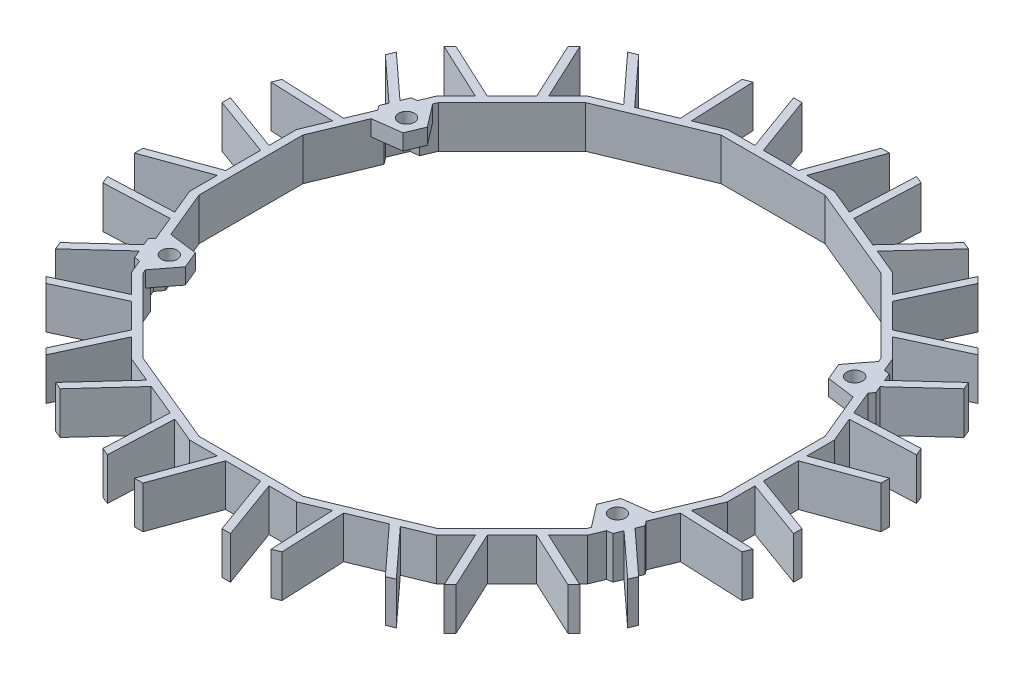
SolidWorks part; units mm, degrees
ref_plane "Front Plane" through (0, 0, 0) normal (0, 0, 1) x (1, 0, 0)
ref_plane "Top Plane" through (0, 0, 0) normal (0, 1, 0) x (1, 0, 0)
ref_plane "Right Plane" through (0, 0, 0) normal (1, 0, 0) x (0, 0, -1)
sketch "Sketch1" plane through (0, 0, 0) normal (0, 1, 0) x (1, 0, 0)
  line L1 (62.5, 12.432) -> (52.9849, 35.4034)
  line L2 (52.9849, 35.4034) -> (35.4034, 52.9849)
  line L3 (35.4034, 52.9849) -> (12.432, 62.5)
  line L4 (12.432, 62.5) -> (-12.432, 62.5)
  line L5 (-12.432, 62.5) -> (-35.4034, 52.9849)
  line L6 (-35.4034, 52.9849) -> (-52.9849, 35.4034)
  line L7 (-52.9849, 35.4034) -> (-62.5, 12.432)
  line L8 (-62.5, 12.432) -> (-62.5, -12.432)
  line L9 (-62.5, -12.432) -> (-52.9849, -35.4034)
  line L10 (-52.9849, -35.4034) -> (-35.4034, -52.9849)
  line L11 (-35.4034, -52.9849) -> (-12.432, -62.5)
  line L12 (-12.432, -62.5) -> (12.432, -62.5)
  line L13 (12.432, -62.5) -> (35.4034, -52.9849)
  line L14 (35.4034, -52.9849) -> (52.9849, -35.4034)
  line L15 (52.9849, -35.4034) -> (62.5, -12.432)
  line L16 (62.5, -12.432) -> (62.5, 12.432)
  circle A0 centre (0, 0) radius 62.5 construction
  dimension "D1" = 125
extrude "Boss-Extrude1" add sketch "Sketch1" along normal blind 1.6
sketch "Sketch2" plane through (0, 0, 0) normal (0, -1, 0) x (1, 0, 0)
  line L0 (-7.5, 62.5) -> (-3.3143, 51)
  line L1 (-12.432, 62.5) -> (12.432, 62.5) construction
  line L2 (-3.3143, 51) -> (3.3143, 51)
  line L3 (3.3143, 51) -> (7.5, 62.5)
  line L4 (7.5, 62.5) -> (9.0963, 62.5)
  line L5 (9.0963, 62.5) -> (4.3647, 49.5)
  line L6 (4.3647, 49.5) -> (-4.3647, 49.5)
  line L7 (-4.3647, 49.5) -> (-9.0963, 62.5)
  line L8 (-9.0963, 62.5) -> (-7.5, 62.5)
  line L131 (15.5139, 61.2235) -> (16.9886, 60.6126)
  line L132 (16.9886, 60.6126) -> (16.4548, 48.3862)
  line L133 (16.4548, 48.3862) -> (22.5789, 45.8495)
  line L134 (22.5789, 45.8495) -> (30.8468, 54.8723)
  line L135 (30.8468, 54.8723) -> (32.3216, 54.2615)
  line L136 (32.3216, 54.2615) -> (22.9752, 44.0618)
  line L137 (22.9752, 44.0618) -> (14.9104, 47.4023)
  line L138 (14.9104, 47.4023) -> (15.5139, 61.2235)
  line L139 (37.7621, 50.6262) -> (38.8909, 49.4975)
  line L140 (38.8909, 49.4975) -> (33.7189, 38.406)
  line L141 (33.7189, 38.406) -> (38.406, 33.7189)
  line L142 (38.406, 33.7189) -> (49.4975, 38.8909)
  line L143 (49.4975, 38.8909) -> (50.6262, 37.7621)
  line L144 (50.6262, 37.7621) -> (38.0881, 31.9155)
  line L145 (38.0881, 31.9155) -> (31.9155, 38.0881)
  line L146 (31.9155, 38.0881) -> (37.7621, 50.6262)
  line L147 (54.2615, 32.3216) -> (54.8723, 30.8468)
  line L148 (54.8723, 30.8468) -> (45.8495, 22.5789)
  line L149 (45.8495, 22.5789) -> (48.3862, 16.4548)
  line L150 (48.3862, 16.4548) -> (60.6126, 16.9886)
  line L151 (60.6126, 16.9886) -> (61.2235, 15.5139)
  line L152 (61.2235, 15.5139) -> (47.4023, 14.9104)
  line L153 (47.4023, 14.9104) -> (44.0618, 22.9752)
  line L154 (44.0618, 22.9752) -> (54.2615, 32.3216)
  line L155 (62.5, 9.0963) -> (62.5, 7.5)
  line L156 (62.5, 7.5) -> (51, 3.3143)
  line L157 (51, 3.3143) -> (51, -3.3143)
  line L158 (51, -3.3143) -> (62.5, -7.5)
  line L167 (62.5, -7.5) -> (62.5, -9.0963)
  line L184 (62.5, -9.0963) -> (49.5, -4.3647)
  line L185 (49.5, -4.3647) -> (49.5, 4.3647)
  line L186 (49.5, 4.3647) -> (62.5, 9.0963)
  line L187 (61.2235, -15.5139) -> (60.6126, -16.9886)
  line L188 (60.6126, -16.9886) -> (48.3862, -16.4548)
  line L189 (48.3862, -16.4548) -> (45.8495, -22.5789)
  line L190 (45.8495, -22.5789) -> (54.8723, -30.8468)
  line L191 (54.8723, -30.8468) -> (54.2615, -32.3216)
  line L192 (54.2615, -32.3216) -> (44.0618, -22.9752)
  line L193 (44.0618, -22.9752) -> (47.4023, -14.9104)
  line L194 (47.4023, -14.9104) -> (61.2235, -15.5139)
  line L195 (50.6262, -37.7621) -> (49.4975, -38.8909)
  line L196 (49.4975, -38.8909) -> (38.406, -33.7189)
  line L197 (38.406, -33.7189) -> (33.7189, -38.406)
  line L198 (33.7189, -38.406) -> (38.8909, -49.4975)
  line L199 (38.8909, -49.4975) -> (37.7621, -50.6262)
  line L200 (37.7621, -50.6262) -> (31.9155, -38.0881)
  line L201 (31.9155, -38.0881) -> (38.0881, -31.9155)
  line L202 (38.0881, -31.9155) -> (50.6262, -37.7621)
  line L203 (32.3216, -54.2615) -> (30.8468, -54.8723)
  line L204 (30.8468, -54.8723) -> (22.5789, -45.8495)
  line L205 (22.5789, -45.8495) -> (16.4548, -48.3862)
  line L206 (16.4548, -48.3862) -> (16.9886, -60.6126)
  line L207 (16.9886, -60.6126) -> (15.5139, -61.2235)
  line L208 (15.5139, -61.2235) -> (14.9104, -47.4023)
  line L209 (14.9104, -47.4023) -> (22.9752, -44.0618)
  line L210 (22.9752, -44.0618) -> (32.3216, -54.2615)
  line L211 (9.0963, -62.5) -> (7.5, -62.5)
  line L212 (7.5, -62.5) -> (3.3143, -51)
  line L213 (3.3143, -51) -> (-3.3143, -51)
  line L214 (-3.3143, -51) -> (-7.5, -62.5)
  line L215 (-7.5, -62.5) -> (-9.0963, -62.5)
  line L216 (-9.0963, -62.5) -> (-4.3647, -49.5)
  line L217 (-4.3647, -49.5) -> (4.3647, -49.5)
  line L218 (4.3647, -49.5) -> (9.0963, -62.5)
  line L219 (-15.5139, -61.2235) -> (-16.9886, -60.6126)
  line L220 (-16.9886, -60.6126) -> (-16.4548, -48.3862)
  line L221 (-16.4548, -48.3862) -> (-22.5789, -45.8495)
  line L222 (-22.5789, -45.8495) -> (-30.8468, -54.8723)
  line L223 (-30.8468, -54.8723) -> (-32.3216, -54.2615)
  line L224 (-32.3216, -54.2615) -> (-22.9752, -44.0618)
  line L225 (-22.9752, -44.0618) -> (-14.9104, -47.4023)
  line L226 (-14.9104, -47.4023) -> (-15.5139, -61.2235)
  line L227 (-37.7621, -50.6262) -> (-38.8909, -49.4975)
  line L228 (-38.8909, -49.4975) -> (-33.7189, -38.406)
  line L229 (-33.7189, -38.406) -> (-38.406, -33.7189)
  line L230 (-38.406, -33.7189) -> (-49.4975, -38.8909)
  line L231 (-49.4975, -38.8909) -> (-50.6262, -37.7621)
  line L232 (-50.6262, -37.7621) -> (-38.0881, -31.9155)
  line L233 (-38.0881, -31.9155) -> (-31.9155, -38.0881)
  line L234 (-31.9155, -38.0881) -> (-37.7621, -50.6262)
  line L235 (-54.2615, -32.3216) -> (-54.8723, -30.8468)
  line L236 (-54.8723, -30.8468) -> (-45.8495, -22.5789)
  line L237 (-45.8495, -22.5789) -> (-48.3862, -16.4548)
  line L238 (-48.3862, -16.4548) -> (-60.6126, -16.9886)
  line L239 (-60.6126, -16.9886) -> (-61.2235, -15.5139)
  line L240 (-61.2235, -15.5139) -> (-47.4023, -14.9104)
  line L241 (-47.4023, -14.9104) -> (-44.0618, -22.9752)
  line L242 (-44.0618, -22.9752) -> (-54.2615, -32.3216)
  line L243 (-62.5, -9.0963) -> (-62.5, -7.5)
  line L244 (-62.5, -7.5) -> (-51, -3.3143)
  line L245 (-51, -3.3143) -> (-51, 3.3143)
  line L246 (-51, 3.3143) -> (-62.5, 7.5)
  line L247 (-62.5, 7.5) -> (-62.5, 9.0963)
  line L248 (-62.5, 9.0963) -> (-49.5, 4.3647)
  line L249 (-49.5, 4.3647) -> (-49.5, -4.3647)
  line L250 (-49.5, -4.3647) -> (-62.5, -9.0963)
  line L251 (-61.2235, 15.5139) -> (-60.6126, 16.9886)
  line L252 (-60.6126, 16.9886) -> (-48.3862, 16.4548)
  line L253 (-48.3862, 16.4548) -> (-45.8495, 22.5789)
  line L254 (-45.8495, 22.5789) -> (-54.8723, 30.8468)
  line L255 (-54.8723, 30.8468) -> (-54.2615, 32.3216)
  line L256 (-54.2615, 32.3216) -> (-44.0618, 22.9752)
  line L257 (-44.0618, 22.9752) -> (-47.4023, 14.9104)
  line L258 (-47.4023, 14.9104) -> (-61.2235, 15.5139)
  line L259 (-50.6262, 37.7621) -> (-49.4975, 38.8909)
  line L260 (-49.4975, 38.8909) -> (-38.406, 33.7189)
  line L261 (-38.406, 33.7189) -> (-33.7189, 38.406)
  line L262 (-33.7189, 38.406) -> (-38.8909, 49.4975)
  line L263 (-38.8909, 49.4975) -> (-37.7621, 50.6262)
  line L264 (-37.7621, 50.6262) -> (-31.9155, 38.0881)
  line L265 (-31.9155, 38.0881) -> (-38.0881, 31.9155)
  line L266 (-38.0881, 31.9155) -> (-50.6262, 37.7621)
  line L267 (-32.3216, 54.2615) -> (-30.8468, 54.8723)
  line L268 (-30.8468, 54.8723) -> (-22.5789, 45.8495)
  line L269 (-22.5789, 45.8495) -> (-16.4548, 48.3862)
  line L270 (-16.4548, 48.3862) -> (-16.9886, 60.6126)
  line L271 (-16.9886, 60.6126) -> (-15.5139, 61.2235)
  line L272 (-15.5139, 61.2235) -> (-14.9104, 47.4023)
  line L273 (-14.9104, 47.4023) -> (-22.9752, 44.0618)
  line L274 (-22.9752, 44.0618) -> (-32.3216, 54.2615)
  point P4 (0, 51)
  point P11 (0, 49.5)
  point P136 (0, 0)
  point P138 (0, 0)
  dimension "D6" = 16
  dimension "D1" = 1.5
  dimension "D2" = 1.5
  dimension "D3" = 15
  dimension "D4" = 40
  dimension "D5" = 11.5
extrude "Boss-Extrude5" add sketch "Sketch2" along normal blind 8
sketch "Sketch6" plane through (0, 1.6, 0) normal (0, 1, 0) x (1, 0, 0)
  line L1 (-42.5, -22.5) -> (42.5, -22.5) construction
  line L2 (-42.5, -22.5) -> (-42.5, 22.5) construction
  line L3 (-42.5, 22.5) -> (42.5, 22.5) construction
  line L4 (42.5, -22.5) -> (42.5, 22.5) construction
  line L5 (-42.5, -22.5) -> (42.5, 22.5) construction
  line L6 (-42.5, 22.5) -> (42.5, -22.5) construction
  circle A0 centre (-42.5, 22.5) radius 1.5
  circle A1 centre (-42.5, -22.5) radius 1.5
  circle A2 centre (42.5, -22.5) radius 1.5
  circle A3 centre (42.5, 22.5) radius 1.5
  point P0 (0, 0)
  dimension "D3" = 3
  dimension "D1" = 85
  dimension "D2" = 45
extrude "Cut-Extrude2" cut sketch "Sketch6" against normal up to surface (1.6 mm away) up to face at (0, 0, 0)
sketch "Sketch17" plane through (0, -8, 0) normal (0, -1, 0) x (1, 0, 0)
  line L1 (-9.8462, 49.5) -> (-28.0395, 41.9641)
  line L2 (-28.0395, 41.9641) -> (-41.9641, 28.0395)
  line L3 (-41.9641, 28.0395) -> (-49.5, 9.8462)
  line L4 (-49.5, 9.8462) -> (-49.5, -9.8462)
  line L5 (-49.5, -9.8462) -> (-41.9641, -28.0395)
  line L6 (-41.9641, -28.0395) -> (-28.0395, -41.9641)
  line L7 (-28.0395, -41.9641) -> (-9.8462, -49.5)
  line L8 (-9.8462, -49.5) -> (9.8462, -49.5)
  line L9 (9.8462, -49.5) -> (28.0395, -41.9641)
  line L10 (28.0395, -41.9641) -> (41.9641, -28.0395)
  line L11 (41.9641, -28.0395) -> (49.5, -9.8462)
  line L12 (49.5, -9.8462) -> (49.5, 9.8462)
  line L13 (49.5, 9.8462) -> (41.9641, 28.0395)
  line L14 (41.9641, 28.0395) -> (28.0395, 41.9641)
  line L15 (28.0395, 41.9641) -> (9.8462, 49.5)
  line L16 (9.8462, 49.5) -> (-9.8462, 49.5)
  line L18 (-49.5, -4.3647) -> (-49.5, 4.3647) construction
  line L20 (-10.1445, 51) -> (-28.8892, 43.2357)
  line L21 (-28.8892, 43.2357) -> (-43.2357, 28.8892)
  line L22 (-43.2357, 28.8892) -> (-51, 10.1445)
  line L23 (-51, 10.1445) -> (-51, -10.1445)
  line L24 (-51, -10.1445) -> (-43.2357, -28.8892)
  line L25 (-43.2357, -28.8892) -> (-28.8892, -43.2357)
  line L26 (-28.8892, -43.2357) -> (-10.1445, -51)
  line L27 (-10.1445, -51) -> (10.1445, -51)
  line L28 (10.1445, -51) -> (28.8892, -43.2357)
  line L29 (28.8892, -43.2357) -> (43.2357, -28.8892)
  line L30 (43.2357, -28.8892) -> (51, -10.1445)
  line L31 (51, -10.1445) -> (51, 10.1445)
  line L32 (51, 10.1445) -> (43.2357, 28.8892)
  line L33 (43.2357, 28.8892) -> (28.8892, 43.2357)
  line L34 (28.8892, 43.2357) -> (10.1445, 51)
  line L35 (10.1445, 51) -> (-10.1445, 51)
  line L36 (-51, 3.3143) -> (-51, -3.3143) construction
  circle A0 centre (0, 0) radius 49.5 construction
  circle A1 centre (0, 0) radius 51 construction
extrude "Boss-Extrude9" add sketch "Sketch17" against normal up to surface (8 mm away) up to face at (-56.75, 0, 0)
sketch "Sketch16" plane through (0, -8, 0) normal (0, -1, 0) x (1, 0, 0)
  line L0 (-49.5, 9.8462) -> (-41.9641, 28.0395) construction
  line L1 (-43.8477, 19.2462) -> (-40.356, 19.7059)
  line L2 (-40.356, 19.7059) -> (-39.0083, 22.9597)
  line L3 (-39.0083, 22.9597) -> (-41.1523, 25.7538)
  line L4 (-41.1523, 25.7538) -> (-44.644, 25.2941)
  line L5 (-44.644, 25.2941) -> (-45.9917, 22.0403)
  line L6 (-45.9917, 22.0403) -> (-43.8477, 19.2462)
  line L7 (0, -0.88) -> (0, 0.88) construction
  line L8 (45.9917, 22.0403) -> (43.8477, 19.2462)
  line L9 (44.644, 25.2941) -> (45.9917, 22.0403)
  line L10 (41.1523, 25.7538) -> (44.644, 25.2941)
  line L11 (39.0083, 22.9597) -> (41.1523, 25.7538)
  line L12 (40.356, 19.7059) -> (39.0083, 22.9597)
  line L13 (43.8477, 19.2462) -> (40.356, 19.7059)
  line L14 (0.88, 0) -> (-0.88, 0) construction
  line L15 (44.644, -25.2941) -> (45.9917, -22.0403)
  line L16 (41.1523, -25.7538) -> (44.644, -25.2941)
  line L17 (39.0083, -22.9597) -> (41.1523, -25.7538)
  line L18 (40.356, -19.7059) -> (39.0083, -22.9597)
  line L19 (43.8477, -19.2462) -> (40.356, -19.7059)
  line L20 (45.9917, -22.0403) -> (43.8477, -19.2462)
  line L21 (-45.9917, -22.0403) -> (-43.8477, -19.2462)
  line L22 (-44.644, -25.2941) -> (-45.9917, -22.0403)
  line L23 (-41.1523, -25.7538) -> (-44.644, -25.2941)
  line L24 (-39.0083, -22.9597) -> (-41.1523, -25.7538)
  line L25 (-40.356, -19.7059) -> (-39.0083, -22.9597)
  line L26 (-43.8477, -19.2462) -> (-40.356, -19.7059)
  circle A0 centre (-42.5, 22.5) radius 3.05 construction
  dimension "D1" = 6.1
extrude "Cut-Extrude5" cut sketch "Sketch16" against normal up to surface (8 mm away) up to face at (42.5, 0, -21)
sketch "Sketch21" plane through (0, 0, 0) normal (0, -1, 0) x (1, 0, 0)
  line L0 (-44.644, 25.2941) -> (-45.9917, 22.0403) construction
  line L1 (-47.1365, 21.8896) -> (-45.4317, 19.6678)
  line L5 (-42.5704, 26.5757) -> (-45.3469, 26.2101)
  line L6 (-45.3469, 26.2101) -> (-47.1365, 21.8896)
  line L7 (-45.9917, 22.0403) -> (-44.9898, 20.7347)
  line L11 (-43.0123, 25.5089) -> (-44.644, 25.2941)
  line L12 (-44.644, 25.2941) -> (-45.9917, 22.0403)
  line L13 (-43.0123, 25.5089) -> (-42.5704, 26.5757)
  line L15 (-43.0123, 25.5089) -> (-41.9641, 28.0395) construction
  line L16 (-44.9898, 20.7347) -> (-45.4317, 19.6678)
  line L17 (-49.5, 9.8462) -> (-44.9898, 20.7347) construction
  line L18 (0, -0.88) -> (0, 0.88) construction
  line L19 (-42.1019, 19.4761) -> (-40.356, 19.7059) [skipped]
  line L20 (-41.9714, 18.4846) -> (-39.6531, 18.7899) [skipped]
  line L21 (-38.7583, 20.9501) -> (-37.8635, 23.1104) [skipped]
  line L22 (-39.6822, 21.3328) -> (-39.0083, 22.9597) [skipped]
  line L23 (-39.0083, 22.9597) -> (-41.1523, 25.7538) [skipped]
  line L24 (-37.8635, 23.1104) -> (-40.7104, 26.8206) [skipped]
  line L25 (43.0123, 25.5089) -> (42.5704, 26.5757)
  line L26 (42.5704, 26.5757) -> (45.3469, 26.2101)
  line L27 (45.3469, 26.2101) -> (47.1365, 21.8896)
  line L28 (47.1365, 21.8896) -> (45.4317, 19.6678)
  line L29 (44.9898, 20.7347) -> (45.4317, 19.6678)
  line L30 (45.9917, 22.0403) -> (44.9898, 20.7347)
  line L31 (44.644, 25.2941) -> (45.9917, 22.0403)
  line L32 (43.0123, 25.5089) -> (44.644, 25.2941)
  line L33 (0.88, 0) -> (-0.88, 0) construction
  line L34 (43.0123, -25.5089) -> (44.644, -25.2941)
  line L35 (44.644, -25.2941) -> (45.9917, -22.0403)
  line L36 (45.9917, -22.0403) -> (44.9898, -20.7347)
  line L37 (44.9898, -20.7347) -> (45.4317, -19.6678)
  line L38 (47.1365, -21.8896) -> (45.4317, -19.6678)
  line L39 (45.3469, -26.2101) -> (47.1365, -21.8896)
  line L40 (42.5704, -26.5757) -> (45.3469, -26.2101)
  line L41 (43.0123, -25.5089) -> (42.5704, -26.5757)
  line L42 (-44.9898, -20.7347) -> (-45.4317, -19.6678)
  line L43 (-43.0123, -25.5089) -> (-42.5704, -26.5757)
  line L44 (-44.644, -25.2941) -> (-45.9917, -22.0403)
  line L45 (-43.0123, -25.5089) -> (-44.644, -25.2941)
  line L46 (-45.9917, -22.0403) -> (-44.9898, -20.7347)
  line L47 (-45.3469, -26.2101) -> (-47.1365, -21.8896)
  line L48 (-42.5704, -26.5757) -> (-45.3469, -26.2101)
  line L49 (-47.1365, -21.8896) -> (-45.4317, -19.6678)
  arc A0 (-42.5814, 26.5492) -> (-45.4208, 19.6943) centre (-42.5, 22.5) ccw construction
  arc A1 (-42.5814, -26.5492) -> (-45.4208, -19.6943) centre (-42.5, -22.5) cw construction
  dimension "D1" = 1
extrude "Boss-Extrude11" add sketch "Sketch21" along normal up to surface (8 mm away) up to face at (0, -8, 0)
sketch "Sketch22" plane through (0, 0, 0) normal (0, -1, 0) x (1, 0, 0)
  line L0 (45.9917, 22.0403) -> (44.644, 25.2941) construction
  line L1 (44.644, 25.2941) -> (41.1523, 25.7538)
  line L2 (41.1523, 25.7538) -> (39.0083, 22.9597)
  line L3 (39.0083, 22.9597) -> (40.356, 19.7059)
  line L4 (40.356, 19.7059) -> (43.8477, 19.2462)
  line L5 (43.8477, 19.2462) -> (45.9917, 22.0403)
  line L6 (45.9917, 22.0403) -> (44.644, 25.2941)
  line L7 (0, -0.88) -> (0, 0.88) construction
  line L8 (-45.9917, 22.0403) -> (-44.644, 25.2941)
  line L9 (-43.8477, 19.2462) -> (-45.9917, 22.0403)
  line L10 (-40.356, 19.7059) -> (-43.8477, 19.2462)
  line L11 (-39.0083, 22.9597) -> (-40.356, 19.7059)
  line L12 (-41.1523, 25.7538) -> (-39.0083, 22.9597)
  line L13 (-44.644, 25.2941) -> (-41.1523, 25.7538)
  line L14 (0.88, 0) -> (-0.88, 0) construction
  line L15 (-44.644, -25.2941) -> (-41.1523, -25.7538)
  line L16 (-41.1523, -25.7538) -> (-39.0083, -22.9597)
  line L17 (-39.0083, -22.9597) -> (-40.356, -19.7059)
  line L18 (-40.356, -19.7059) -> (-43.8477, -19.2462)
  line L19 (-43.8477, -19.2462) -> (-45.9917, -22.0403)
  line L20 (-45.9917, -22.0403) -> (-44.644, -25.2941)
  line L21 (45.9917, -22.0403) -> (44.644, -25.2941)
  line L22 (43.8477, -19.2462) -> (45.9917, -22.0403)
  line L23 (40.356, -19.7059) -> (43.8477, -19.2462)
  line L24 (39.0083, -22.9597) -> (40.356, -19.7059)
  line L25 (41.1523, -25.7538) -> (39.0083, -22.9597)
  line L26 (44.644, -25.2941) -> (41.1523, -25.7538)
  circle A0 centre (42.5, 22.5) radius 3.05 construction
  circle A1 centre (42.5, 22.5) radius 1.5
  circle A2 centre (42.5, 22.5) radius 1.5 construction
  circle A3 centre (42.5, -22.5) radius 3.05 construction
  circle A4 centre (42.5, -22.5) radius 1.5
  circle A5 centre (-42.5, 22.5) radius 1.5
  circle A6 centre (-42.5, -22.5) radius 1.5
extrude "Boss-Extrude12" add sketch "Sketch22" along normal blind 3
sketch "Sketch23" plane through (0, -3, 0) normal (0, -1, 0) x (1, 0, 0)
  line L0 (-41.1523, 25.7538) -> (-42.2943, 27.2422)
  line L1 (-43.0123, 25.5089) -> (-41.9641, 28.0395) construction
  line L2 (-43.8477, 19.2462) -> (-45.7078, 19.0014)
  line L3 (-49.5, 9.8462) -> (-44.9898, 20.7347) construction
  line L4 (-43.8477, 19.2462) -> (-40.356, 19.7059) construction
  line L5 (-39.0083, 22.9597) -> (-41.1523, 25.7538) construction
  line L6 (-42.2943, 27.2422) -> (-43.0123, 25.5089)
  line L7 (-43.0123, 25.5089) -> (-41.1523, 25.7538)
  line L8 (-44.9898, 20.7347) -> (-43.8477, 19.2462)
  line L9 (-45.7078, 19.0014) -> (-44.9898, 20.7347)
  line L10 (5.28, 0) -> (-5.28, 0) construction
  line L11 (-43.8477, -19.2462) -> (-45.7078, -19.0014)
  line L12 (-44.9898, -20.7347) -> (-43.8477, -19.2462)
  line L13 (-45.7078, -19.0014) -> (-44.9898, -20.7347)
  line L14 (-42.2943, -27.2422) -> (-43.0123, -25.5089)
  line L15 (-41.1523, -25.7538) -> (-42.2943, -27.2422)
  line L16 (-43.0123, -25.5089) -> (-41.1523, -25.7538)
  line L17 (0, -5.28) -> (0, 5.28) construction
  line L18 (43.0123, -25.5089) -> (41.1523, -25.7538)
  line L19 (41.1523, -25.7538) -> (42.2943, -27.2422)
  line L20 (42.2943, -27.2422) -> (43.0123, -25.5089)
  line L21 (45.7078, -19.0014) -> (44.9898, -20.7347)
  line L22 (44.9898, -20.7347) -> (43.8477, -19.2462)
  line L23 (43.8477, -19.2462) -> (45.7078, -19.0014)
  line L24 (45.7078, 19.0014) -> (44.9898, 20.7347)
  line L25 (44.9898, 20.7347) -> (43.8477, 19.2462)
  line L26 (43.0123, 25.5089) -> (41.1523, 25.7538)
  line L27 (42.2943, 27.2422) -> (43.0123, 25.5089)
  line L28 (43.8477, 19.2462) -> (45.7078, 19.0014)
  line L29 (41.1523, 25.7538) -> (42.2943, 27.2422)
extrude "Boss-Extrude13" add sketch "Sketch23" against normal up to surface (3 mm away) up to face at (-47.0303, 0, -30.5306)
sketch "Sketch24" plane through (0, 0, 0) normal (0, -1, 0) x (1, 0, 0)
  line L0 (-12.432, 62.5) -> (-15.5139, 61.2235)
  line L1 (-15.5139, 61.2235) -> (-14.98, 48.9971)
  line L2 (-14.98, 48.9971) -> (-10.1445, 51)
  line L3 (-10.1445, 51) -> (-4.9106, 51)
  line L4 (-4.9106, 51) -> (-9.0963, 62.5)
  line L5 (-9.0963, 62.5) -> (-12.432, 62.5)
  line L6 (15.5139, 61.2235) -> (12.432, 62.5)
  line L7 (12.432, 62.5) -> (9.0963, 62.5)
  line L8 (9.0963, 62.5) -> (4.9106, 51)
  line L9 (4.9106, 51) -> (10.1445, 51)
  line L10 (10.1445, 51) -> (14.98, 48.9971)
  line L11 (14.98, 48.9971) -> (15.5139, 61.2235)
  line L12 (37.7621, 50.6262) -> (35.4034, 52.9849)
  line L13 (35.4034, 52.9849) -> (32.3216, 54.2615)
  line L14 (32.3216, 54.2615) -> (24.0537, 45.2386)
  line L15 (24.0537, 45.2386) -> (28.8892, 43.2357)
  line L16 (28.8892, 43.2357) -> (32.5901, 39.5348)
  line L17 (32.5901, 39.5348) -> (37.7621, 50.6262)
  line L18 (54.2615, 32.3216) -> (52.9849, 35.4034)
  line L19 (52.9849, 35.4034) -> (50.6262, 37.7621)
  line L20 (50.6262, 37.7621) -> (39.5348, 32.5901)
  line L21 (39.5348, 32.5901) -> (43.2357, 28.8892)
  line L22 (43.2357, 28.8892) -> (45.2386, 24.0537)
  line L23 (45.2386, 24.0537) -> (54.2615, 32.3216)
  line L24 (62.5, 9.0963) -> (62.5, 12.432)
  line L25 (62.5, 12.432) -> (61.2235, 15.5139)
  line L26 (61.2235, 15.5139) -> (48.9971, 14.98)
  line L27 (48.9971, 14.98) -> (51, 10.1445)
  line L28 (51, 10.1445) -> (51, 4.9106)
  line L29 (51, 4.9106) -> (62.5, 9.0963)
  line L30 (61.2235, -15.5139) -> (62.5, -12.432)
  line L31 (62.5, -12.432) -> (62.5, -9.0963)
  line L32 (62.5, -9.0963) -> (51, -4.9106)
  line L33 (51, -4.9106) -> (51, -10.1445)
  line L34 (51, -10.1445) -> (48.9971, -14.98)
  line L35 (48.9971, -14.98) -> (61.2235, -15.5139)
  line L36 (50.6262, -37.7621) -> (52.9849, -35.4034)
  line L37 (52.9849, -35.4034) -> (54.2615, -32.3216)
  line L38 (54.2615, -32.3216) -> (45.2386, -24.0537)
  line L39 (45.2386, -24.0537) -> (43.2357, -28.8892)
  line L40 (43.2357, -28.8892) -> (39.5348, -32.5901)
  line L41 (39.5348, -32.5901) -> (50.6262, -37.7621)
  line L42 (32.3216, -54.2615) -> (35.4034, -52.9849)
  line L43 (35.4034, -52.9849) -> (37.7621, -50.6262)
  line L44 (37.7621, -50.6262) -> (32.5901, -39.5348)
  line L45 (32.5901, -39.5348) -> (28.8892, -43.2357)
  line L46 (28.8892, -43.2357) -> (24.0537, -45.2386)
  line L47 (24.0537, -45.2386) -> (32.3216, -54.2615)
  line L48 (9.0963, -62.5) -> (12.432, -62.5)
  line L49 (12.432, -62.5) -> (15.5139, -61.2235)
  line L50 (15.5139, -61.2235) -> (14.98, -48.9971)
  line L51 (14.98, -48.9971) -> (10.1445, -51)
  line L52 (10.1445, -51) -> (4.9106, -51)
  line L53 (4.9106, -51) -> (9.0963, -62.5)
  line L54 (-15.5139, -61.2235) -> (-12.432, -62.5)
  line L55 (-12.432, -62.5) -> (-9.0963, -62.5)
  line L56 (-9.0963, -62.5) -> (-4.9106, -51)
  line L57 (-4.9106, -51) -> (-10.1445, -51)
  line L58 (-10.1445, -51) -> (-14.98, -48.9971)
  line L59 (-14.98, -48.9971) -> (-15.5139, -61.2235)
  line L60 (-37.7621, -50.6262) -> (-35.4034, -52.9849)
  line L61 (-35.4034, -52.9849) -> (-32.3216, -54.2615)
  line L62 (-32.3216, -54.2615) -> (-24.0537, -45.2386)
  line L63 (-24.0537, -45.2386) -> (-28.8892, -43.2357)
  line L64 (-28.8892, -43.2357) -> (-32.5901, -39.5348)
  line L65 (-32.5901, -39.5348) -> (-37.7621, -50.6262)
  line L66 (-54.2615, -32.3216) -> (-52.9849, -35.4034)
  line L67 (-52.9849, -35.4034) -> (-50.6262, -37.7621)
  line L68 (-50.6262, -37.7621) -> (-39.5348, -32.5901)
  line L69 (-39.5348, -32.5901) -> (-43.2357, -28.8892)
  line L70 (-43.2357, -28.8892) -> (-45.2386, -24.0537)
  line L71 (-45.2386, -24.0537) -> (-54.2615, -32.3216)
  line L72 (-62.5, -9.0963) -> (-62.5, -12.432)
  line L73 (-62.5, -12.432) -> (-61.2235, -15.5139)
  line L74 (-61.2235, -15.5139) -> (-48.9971, -14.98)
  line L75 (-48.9971, -14.98) -> (-51, -10.1445)
  line L76 (-51, -10.1445) -> (-51, -4.9106)
  line L77 (-51, -4.9106) -> (-62.5, -9.0963)
  line L78 (-61.2235, 15.5139) -> (-62.5, 12.432)
  line L79 (-62.5, 12.432) -> (-62.5, 9.0963)
  line L80 (-62.5, 9.0963) -> (-51, 4.9106)
  line L81 (-51, 4.9106) -> (-51, 10.1445)
  line L82 (-51, 10.1445) -> (-48.9971, 14.98)
  line L83 (-48.9971, 14.98) -> (-61.2235, 15.5139)
  line L84 (-50.6262, 37.7621) -> (-52.9849, 35.4034)
  line L85 (-52.9849, 35.4034) -> (-54.2615, 32.3216)
  line L86 (-54.2615, 32.3216) -> (-45.2386, 24.0537)
  line L87 (-45.2386, 24.0537) -> (-43.2357, 28.8892)
  line L88 (-43.2357, 28.8892) -> (-39.5348, 32.5901)
  line L89 (-39.5348, 32.5901) -> (-50.6262, 37.7621)
  line L90 (-32.3216, 54.2615) -> (-35.4034, 52.9849)
  line L91 (-35.4034, 52.9849) -> (-37.7621, 50.6262)
  line L92 (-37.7621, 50.6262) -> (-32.5901, 39.5348)
  line L93 (-32.5901, 39.5348) -> (-28.8892, 43.2357)
  line L94 (-28.8892, 43.2357) -> (-24.0537, 45.2386)
  line L95 (-24.0537, 45.2386) -> (-32.3216, 54.2615)
  point P104 (0, 0)
  dimension "D1" = 16
extrude "Boss-Extrude15" [suppressed] add sketch "Sketch24" along normal blind 1.5
sketch "Sketch18" plane through (0, 1.6, 0) normal (0, 1, 0) x (1, 0, 0)
  line L0 (-62.5, 12.432) -> (-62.5, -12.432) construction
  line L1 (-35.4034, 52.9849) -> (-52.9849, 35.4034)
  line L2 (-52.9849, 35.4034) -> (-62.5, 12.432)
  line L3 (-62.5, 12.432) -> (-62.5, -12.432)
  line L4 (-62.5, -12.432) -> (-52.9849, -35.4034)
  line L5 (-52.9849, -35.4034) -> (-35.4034, -52.9849)
  line L6 (-35.4034, -52.9849) -> (-12.432, -62.5)
  line L7 (-12.432, -62.5) -> (12.432, -62.5)
  line L8 (12.432, -62.5) -> (35.4034, -52.9849)
  line L9 (35.4034, -52.9849) -> (52.9849, -35.4034)
  line L10 (52.9849, -35.4034) -> (62.5, -12.432)
  line L11 (62.5, -12.432) -> (62.5, 12.432)
  line L12 (62.5, 12.432) -> (52.9849, 35.4034)
  line L13 (52.9849, 35.4034) -> (35.4034, 52.9849)
  line L14 (35.4034, 52.9849) -> (12.432, 62.5)
  line L15 (12.432, 62.5) -> (-12.432, 62.5)
  line L16 (-12.432, 62.5) -> (-35.4034, 52.9849)
  circle A0 centre (0, 0) radius 62.5 construction
extrude "Cut-Extrude6" cut sketch "Sketch18" against normal up to surface (1.6 mm away) up to face at (-47.0303, 0, -30.5306)
